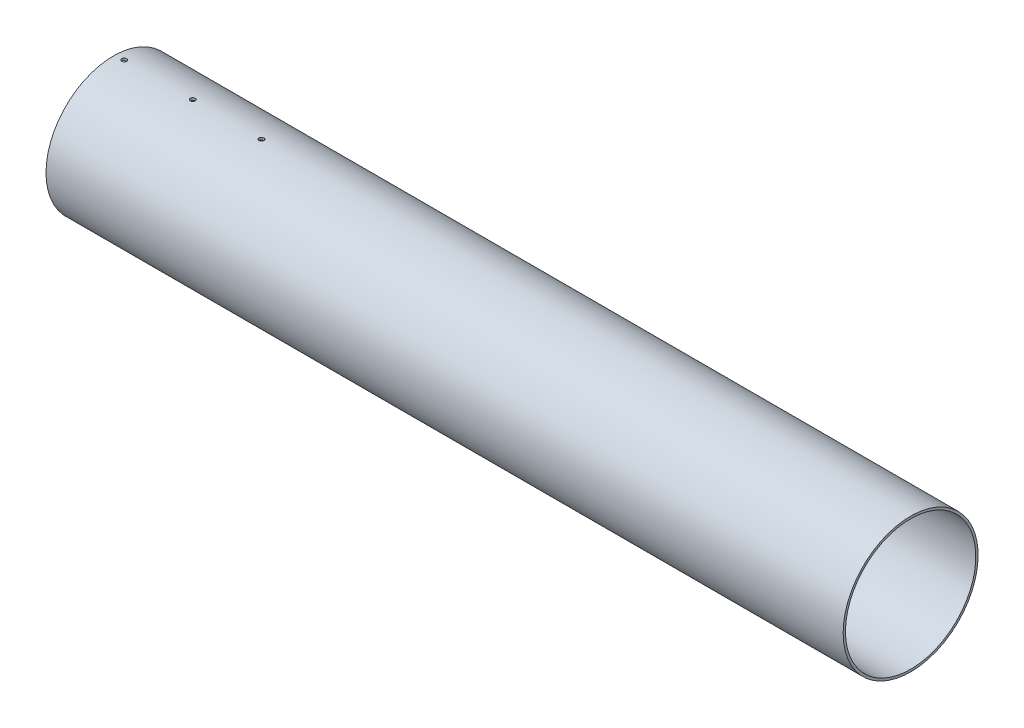
SolidWorks part; units mm, degrees
ref_plane "Plan de face" through (0, 0, 0) normal (0, 0, 1) x (1, 0, 0)
ref_plane "Plan de dessus" through (0, 0, 0) normal (0, 1, 0) x (1, 0, 0)
ref_plane "Plan de droite" through (0, 0, 0) normal (1, 0, 0) x (0, 0, -1)
sketch "Esquisse1" plane through (0, 0, 0) normal (0, 0, 1) x (1, 0, 0)
  line L0 (0, 0) -> (0, 76.2) construction
  line L1 (0, 0) -> (142.5133, 0) construction
  line L2 (0, 76.2) -> (900, 76.2)
  line L3 (0, 76.2) -> (0, -76.2) construction
  line L4 (0, 73.6092) -> (900, 73.6092)
  line L5 (900, 76.2) -> (900, 73.6092)
  line L6 (0, -76.2) -> (900, -76.2) construction
  line L7 (0, 76.2) -> (0, 73.6092)
  dimension "D1" = 152.4
  dimension "D2" = 2.5908
  dimension "D3" = 900
revolve "Révolution1" add sketch "Esquisse1" angle 360 about L1
ref_plane "Plan2" through (0, 76.2, 0) normal (0, 1, 0) x (1, 0, 0)
hole_wizard "Dégagement M51" positions "Esquisse2" profile "Esquisse3" hole size "M5" standard "DIN"
sketch "Esquisse2" plane through (0, 76.2, 0) normal (0, 1, 0) x (1, 0, 0)
  point P0 (165, 2.0619)
  point P3 (87.5, 2.0619)
  point P6 (10, 2.0619)
sketch "Esquisse3" plane through (165, 76.2, -2.0619) normal (1, 0, 0) x (0, 0, 1)
  line L0 (0, 0) -> (0, 11.6524)
  line L1 (0, 11.6524) -> (2.75, 10)
  line L2 (2.75, 10) -> (2.75, 0)
  line L5 (2.75, 0) -> (0, 0)
  line L10 (0, 11.6524) -> (-2.75, 10) construction
  line L11 (0, -6.35) -> (0, 107.95) construction
  dimension "Diamètre du perçage" = 5.5
  dimension "Profondeur du perçage" = 10
  dimension "Angle de pointe" = 118
